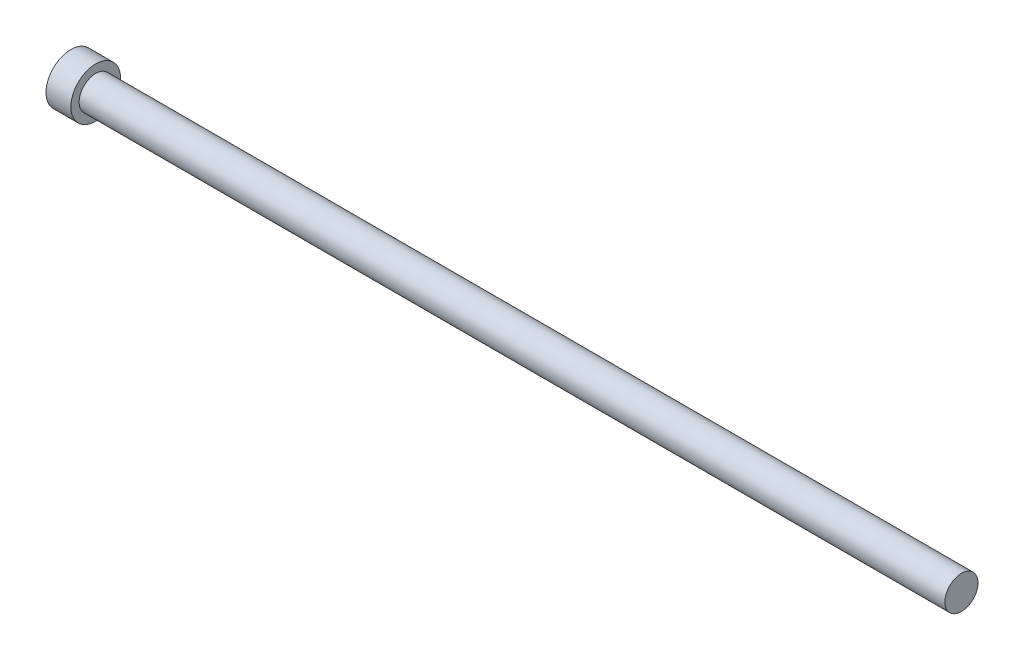
SolidWorks part; units mm, degrees
material "Brass"
ref_plane "Front Plane" through (0, 0, 0) normal (0, 0, 1) x (1, 0, 0)
ref_plane "Top Plane" through (0, 0, 0) normal (0, 1, 0) x (1, 0, 0)
ref_plane "Right Plane" through (0, 0, 0) normal (1, 0, 0) x (0, 0, -1)
sketch "Sketch1" plane through (0, 0, 0) normal (0, 0, 1) x (1, 0, 0)
  line L0 (0, 0) -> (215, 0)
  line L1 (6, 6) -> (6, 4)
  line L2 (215, 0) -> (215, 4)
  line L3 (0, 0) -> (0, 6)
  line L4 (0, 6) -> (6, 6)
  line L6 (6, 4) -> (215, 4)
revolve "Revolve1" add sketch "Sketch1" angle 360 about L0
